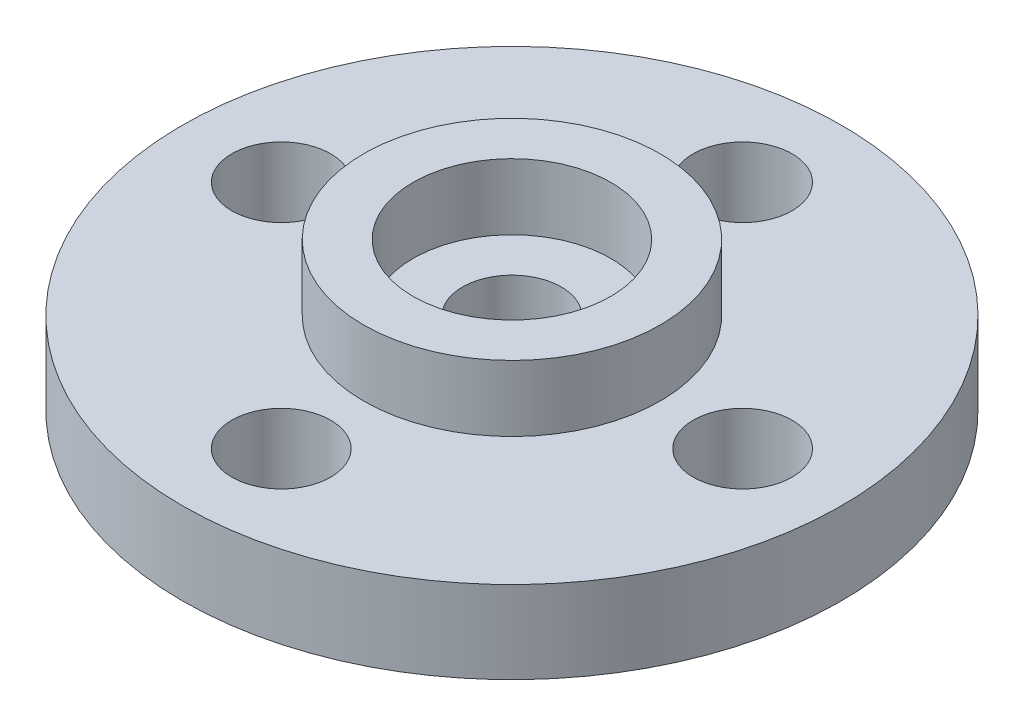
SolidWorks part; units mm, degrees
ref_plane "前视基准面" through (0, 0, 0) normal (0, 0, 1) x (1, 0, 0)
ref_plane "上视基准面" through (0, 0, 0) normal (0, 1, 0) x (1, 0, 0)
ref_plane "右视基准面" through (0, 0, 0) normal (1, 0, 0) x (0, 0, -1)
other "Configuration Table"
sketch "草图1" plane through (0, 0, 0) normal (0, 1, 0) x (1, 0, 0)
  circle A0 centre (0, 0) radius 10
  circle A1 centre (0, 0) radius 7 construction
  circle A2 centre (0, 0) radius 1.5
  circle A3 centre (0, 7) radius 1.5
  circle A4 centre (7, 0) radius 1.5
  circle A5 centre (0, -7) radius 1.5
  circle A6 centre (-7, 0) radius 1.5
  point P7 (-12.8568, -2.7318)
  point P16 (0, 0)
  dimension "D2" = 14
  dimension "D3" = 3
  dimension "D4" = 20
  dimension "D1" = 4
extrude "凸台-拉伸1" add sketch "草图1" along normal blind 2.5 contours A0 A6 A5 A4 A3 A2
sketch "草图2" plane through (0, 2.5, 0) normal (0, 1, 0) x (1, 0, 0)
  circle A0 centre (0, 0) radius 3
  circle A1 centre (0, 0) radius 4.5
  dimension "D1" = 9
  dimension "D2" = 6
extrude "凸台-拉伸2" add sketch "草图2" along normal blind 2
